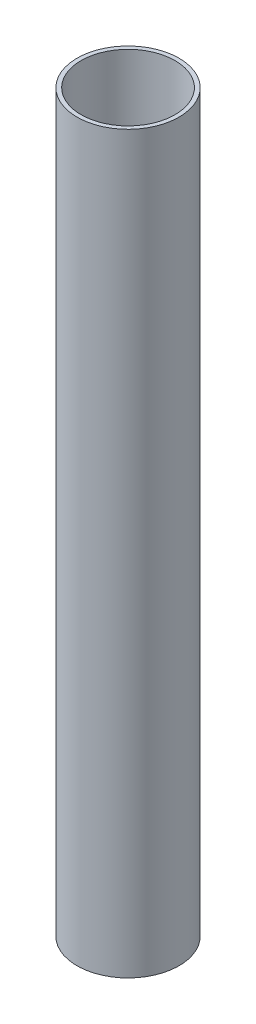
SolidWorks part; units mm, degrees
ref_plane "前视基准面" through (0, 0, 0) normal (0, 0, 1) x (1, 0, 0)
ref_plane "上视基准面" through (0, 0, 0) normal (0, 1, 0) x (1, 0, 0)
ref_plane "右视基准面" through (0, 0, 0) normal (1, 0, 0) x (0, 0, -1)
sketch "草图1" plane through (0, 0, 0) normal (0, 1, 0) x (1, 0, 0)
  circle A0 centre (0, 0) radius 12.5
  circle A1 centre (0, 0) radius 11.5
  dimension "D1" = 25
  dimension "D2" = 23
extrude "凸台-拉伸1" add sketch "草图1" along normal blind 180
